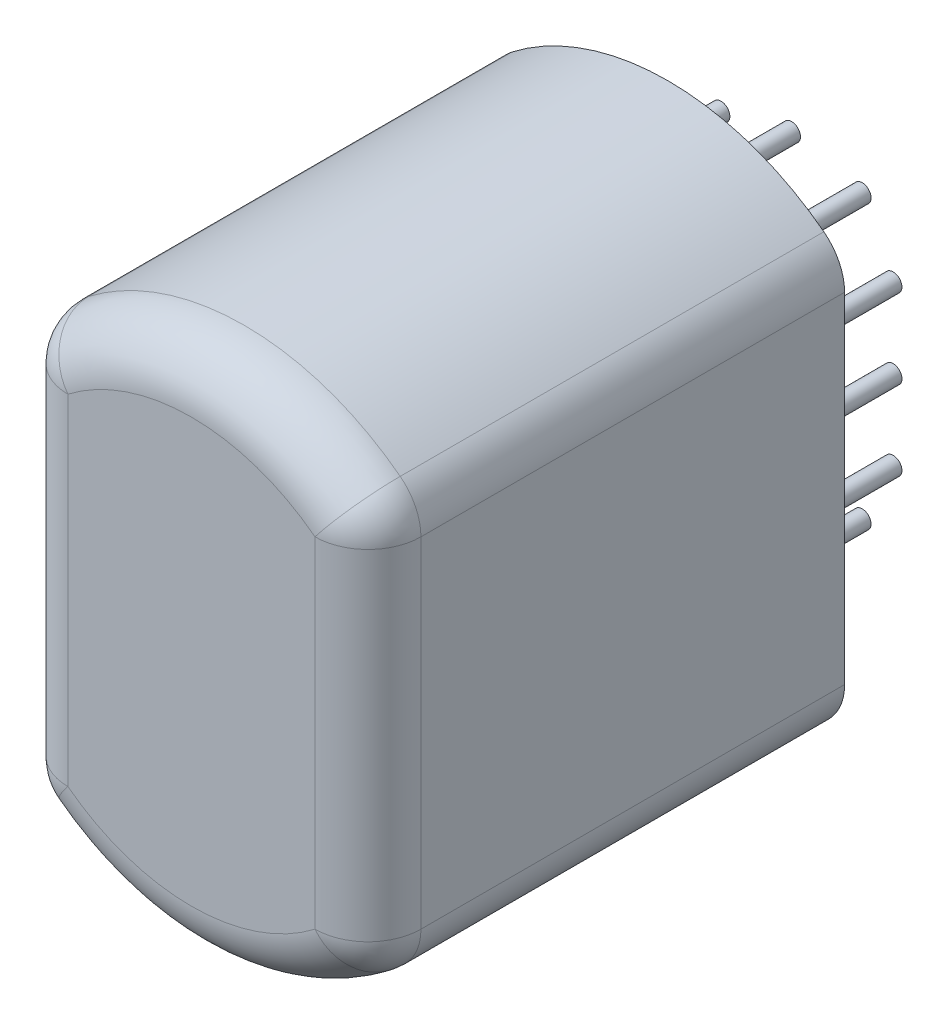
SolidWorks part; units mm, degrees
ref_plane "Front Plane" through (0, 0, 0) normal (0, 0, 1) x (1, 0, 0)
ref_plane "Top Plane" through (0, 0, 0) normal (0, 1, 0) x (1, 0, 0)
ref_plane "Right Plane" through (0, 0, 0) normal (1, 0, 0) x (0, 0, -1)
sketch "Sketch1" plane through (0, 0, 0) normal (0, 0, 1) x (1, 0, 0)
  line L0 (0, 15) -> (0, -15) construction
  line L2 (-10, -11) -> (-10, 11)
  line L4 (10, -11) -> (10, 11)
  line L5 (-10, -11) -> (10, 11) construction
  line L6 (-10, 11) -> (10, -11) construction
  arc A0 (-10, 11) -> (10, 11) centre (0, 0.5) cw
  arc A1 (-10, -11) -> (10, -11) centre (0, -0.5) ccw
  point P0 (0, 0)
  dimension "D1" = 30
  dimension "D2" = 22
  dimension "D3" = 20
extrude "Boss-Extrude1" add sketch "Sketch1" along normal blind 27
fillet "Fillet1" radius 3 4 edges at (10, -11, 13.5) (-10, -11, 13.5) (-10, 11, 13.5) (10, 11, 13.5)
fillet "Fillet2" radius 3 8 edges at (-9.6906, -10.9511, 27) (-10, 0, 27) (-9.6906, 10.9511, 27) (0, 15, 27) (9.6906, 10.9511, 27) (10, 0, 27) (9.6906, -10.9511, 27) (0, -15, 27)
ref_plane "Plane1" through (10, 9.6241, 0) normal (0, 1, 0) x (1, 0, 0)
sketch "Sketch3" plane through (0, 0, 0) normal (0, 0, -1) x (-1, 0, 0)
  circle A0 centre (0, 0) radius 1.75
  dimension "D1" = 3.5
extrude "Boss-Extrude2" add sketch "Sketch3" along normal blind 7
sketch "Sketch4" plane through (0, 0, 0) normal (0, 0, -1) x (-1, 0, 0)
  line L0 (0, 0) -> (-5.75, 0) construction
  line L1 (0, 0) -> (0, 9) construction
  line L2 (-5.75, 0) -> (-5.75, 4.5) construction
  circle A0 centre (-5.75, 0) radius 0.5
  circle A1 centre (-5.75, 4.5) radius 0.5
  circle A2 centre (-4, 8) radius 0.5
  circle A3 centre (0, 9) radius 0.5
  point P12 (-3.6314, 0)
  dimension "D1" = 1
  dimension "D2" = 9
  dimension "D3" = 11.5
  dimension "D4" = 8
  dimension "D5" = 16
  dimension "D6" = 18
extrude "Boss-Extrude3" add sketch "Sketch4" along normal blind 7 separate body
mirror "Mirror1" about plane through (0, 0, 0) normal (1, 0, 0) of bodies 105 104 103
mirror "Mirror2" about plane through (0, 0, 0) normal (0, 1, 0) of bodies 104 105 106 107 108
combine bodies "Combine1" operation type add bodies to combine 103 106 108 110 114 104 107 113 105 112 109 111 102
